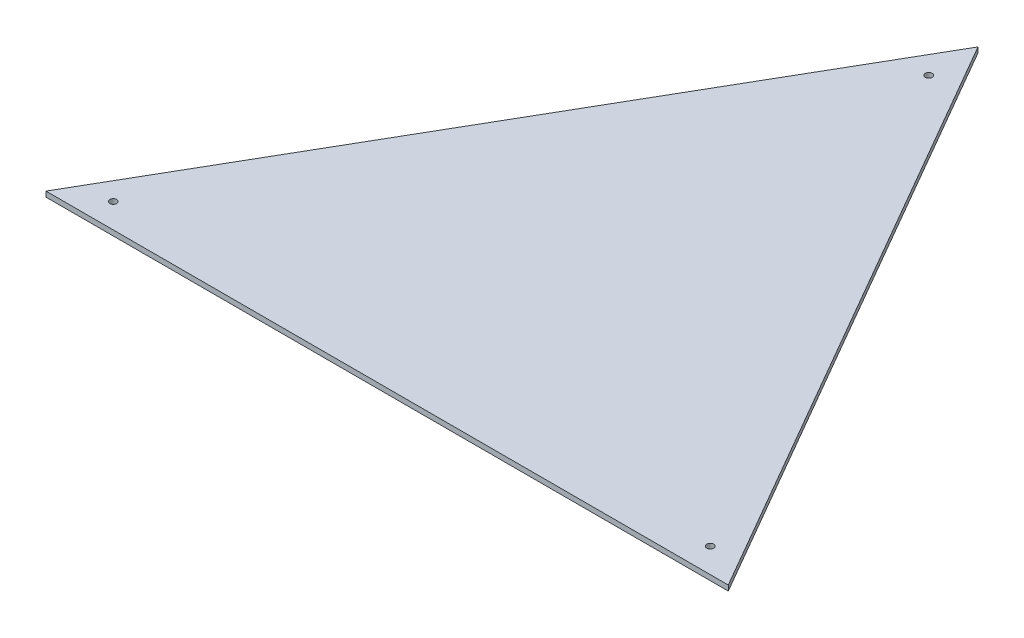
SolidWorks part; units mm, degrees
ref_plane "Front Plane" through (0, 0, 0) normal (0, 0, 1) x (1, 0, 0)
ref_plane "Top Plane" through (0, 0, 0) normal (0, 1, 0) x (1, 0, 0)
ref_plane "Right Plane" through (0, 0, 0) normal (1, 0, 0) x (0, 0, -1)
sketch "Sketch1" plane through (0, 0, 0) normal (0, 1, 0) x (1, 0, 0)
  line L1 (0, 355.6) -> (-307.9586, -177.8)
  line L2 (-307.9586, -177.8) -> (307.9586, -177.8)
  line L3 (307.9586, -177.8) -> (0, 355.6)
  circle A0 centre (0, 0) radius 177.8 construction
  dimension "D1" = 355.6
extrude "Boss-Extrude1" add sketch "Sketch1" along normal blind 4.7625
sketch "Sketch2" plane through (0, 4.7625, 0) normal (0, 1, 0) x (1, 0, 0)
  line L0 (0, 355.6) -> (-307.9586, -177.8) construction
  line L4 (307.9586, -177.8) -> (0, 355.6) construction
  line L5 (-307.9586, -177.8) -> (307.9586, -177.8) construction
  circle A0 centre (0, 311.15) radius 3.175
  circle A1 centre (-269.4638, -155.575) radius 3.175
  circle A2 centre (269.4638, -155.575) radius 3.175
  dimension "D2" = 19.05
  dimension "D3" = 6.35
  dimension "D4" = 6.35
  dimension "D6" = 19.05
  dimension "D7" = 19.05
  dimension "D8" = 19.05
  dimension "D9" = 6.35
  dimension "D1" = 19.05
  dimension "D5" = 19.05
extrude "Cut-Extrude1" cut sketch "Sketch2" against normal through all
